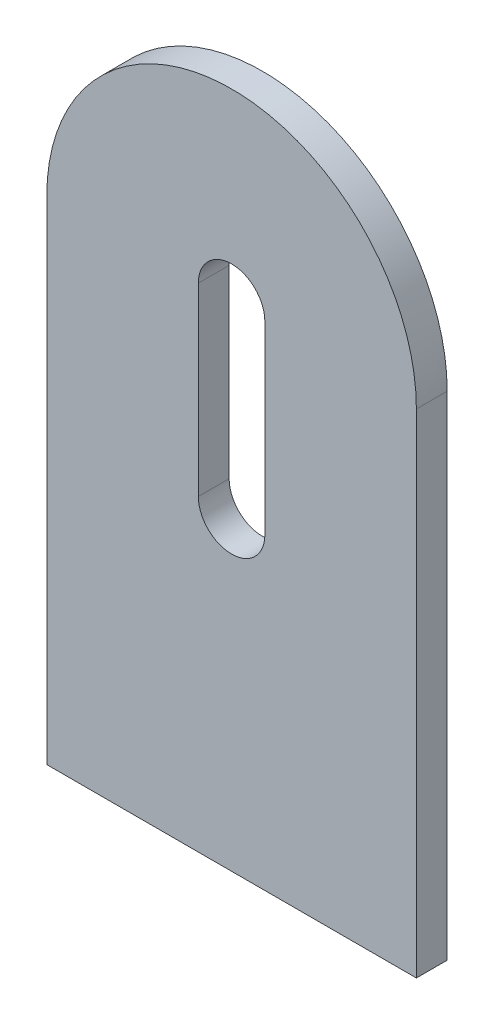
SolidWorks part; units mm, degrees
ref_plane "Front Plane" through (0, 0, 0) normal (0, 0, 1) x (1, 0, 0)
ref_plane "Top Plane" through (0, 0, 0) normal (0, 1, 0) x (1, 0, 0)
ref_plane "Right Plane" through (0, 0, 0) normal (1, 0, 0) x (0, 0, -1)
sketch "Sketch1" plane through (0, 0, 0) normal (0, 0, 1) x (1, 0, 0)
  line L0 (15.621, 50.8) -> (15.621, 31.75)
  line L1 (0, 0) -> (38.1, 0)
  line L2 (0, 0) -> (0, 50.8)
  line L4 (38.1, 0) -> (38.1, 50.8)
  line L5 (22.479, 31.75) -> (22.479, 50.8)
  arc A0 (0, 50.8) -> (38.1, 50.8) centre (19.05, 50.8) cw
  arc A1 (22.479, 50.8) -> (15.621, 50.8) centre (19.05, 50.8) ccw
  arc A2 (15.621, 31.75) -> (22.479, 31.75) centre (19.05, 31.75) ccw
  dimension "D2" = 6.858
  dimension "D5" = 19.05
  dimension "D1" = 38.1
  dimension "D3" = 19.05
  dimension "D4" = 50.8
extrude "Boss-Extrude1" add sketch "Sketch1" along normal blind 3.175
